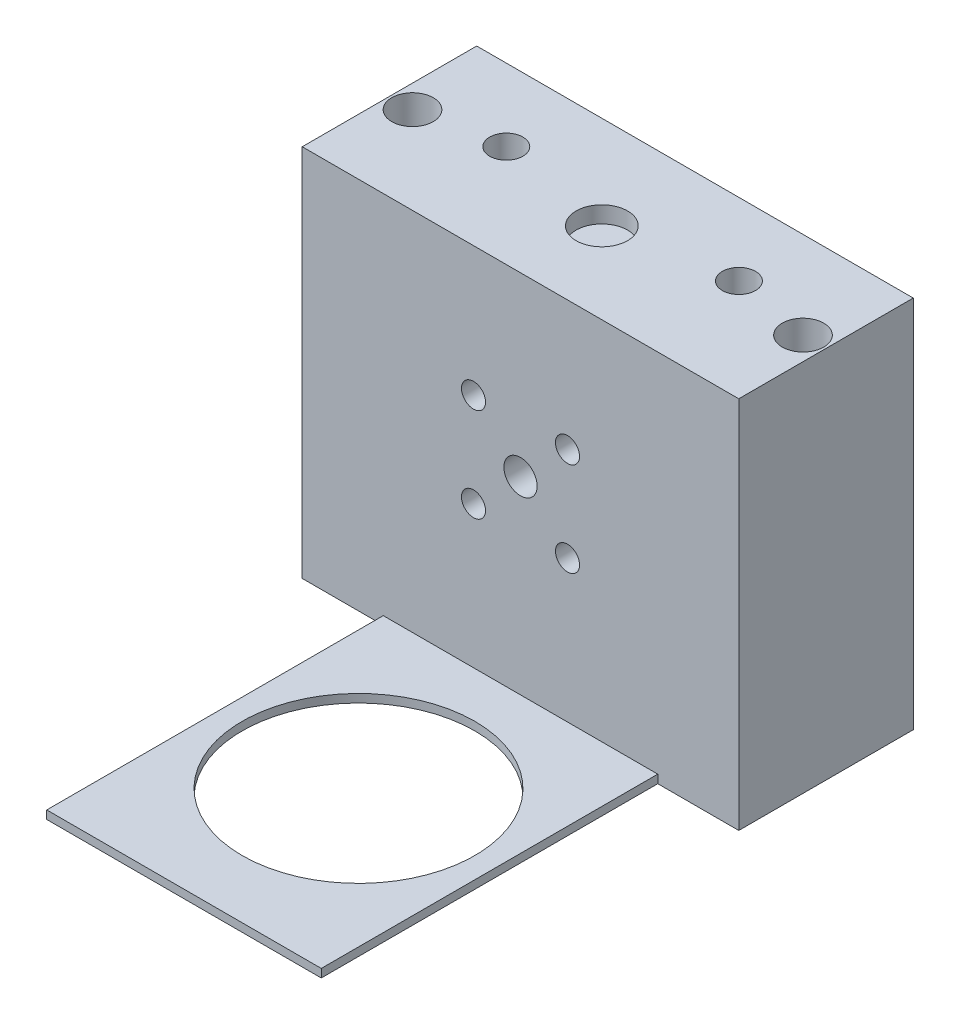
SolidWorks part; units mm, degrees
ref_plane "Front Plane" through (0, 0, 0) normal (0, 0, 1) x (1, 0, 0)
ref_plane "Top Plane" through (0, 0, 0) normal (0, 1, 0) x (1, 0, 0)
ref_plane "Right Plane" through (0, 0, 0) normal (1, 0, 0) x (0, 0, -1)
sketch "Sketch1" plane through (0, 0, 0) normal (0, 1, 0) x (1, 0, 0)
  line L0 (-23.5, 0) -> (23.5, 0) construction
  line L1 (-26.27, -10.5) -> (26.27, -10.5)
  line L2 (-26.27, -10.5) -> (-26.27, 10.5)
  line L3 (-26.27, 10.5) -> (26.27, 10.5)
  line L4 (26.27, -10.5) -> (26.27, 10.5)
  line L5 (-26.27, -10.5) -> (26.27, 10.5) construction
  line L6 (-26.27, 10.5) -> (26.27, -10.5) construction
  circle A0 centre (23.5, 0) radius 2.5
  circle A1 centre (-23.5, 0) radius 2.5
  point P0 (0, 0)
  dimension "D4" = 5
  dimension "D1" = 21
  dimension "D2" = 52.54
  dimension "D3" = 47
extrude "Boss-Extrude1" add sketch "Sketch1" along normal blind 45
sketch "Sketch2" plane through (0, 0, -10.5) normal (0, 0, -1) x (-1, 0, 0)
  line L0 (-26.27, 45) -> (26.27, 45) construction
  circle A0 centre (0, 23.75) radius 2
  point P2 (0, 0)
  dimension "D1" = 4
  dimension "D2" = 21.25
extrude "Cut-Extrude1" cut sketch "Sketch2" against normal through all
sketch "Sketch3" plane through (0, 45, 0) normal (0, 1, 0) x (1, 0, 0)
  line L0 (-14, 1.79) -> (14, 1.79) construction
  circle A0 centre (-14, 1.79) radius 2
  circle A1 centre (14, 1.79) radius 2
  point P4 (0, 1.79)
  point P5 (0, 0)
  point P11 (0, 0)
  dimension "D1" = 4
  dimension "D2" = 28
  dimension "D3" = 1.79
extrude "Cut-Extrude2" cut sketch "Sketch3" against normal blind 5
sketch "Sketch4" plane through (0, 0, -10.5) normal (0, 0, -1) x (-1, 0, 0)
  line L0 (-5.6569, 18.0931) -> (5.6569, 18.0931) construction
  line L1 (5.6569, 18.0931) -> (5.6569, 29.4069) construction
  line L2 (5.6569, 29.4069) -> (-5.6569, 29.4069) construction
  line L3 (-5.6569, 29.4069) -> (-5.6569, 18.0931) construction
  line L4 (-26.27, 45) -> (26.27, 45) construction
  circle A0 centre (0, 23.75) radius 8 construction
  point P3 (-5.6569, 18.0931)
  point P4 (-5.6569, 29.4069)
  point P5 (5.6569, 29.4069)
  point P6 (5.6569, 18.0931)
  point P11 (5.6569, 18.6569)
  point P12 (5.6569, 18.6569)
  point P13 (3.7347, 5.9252)
  dimension "D1" = 16
  dimension "D2" = 0
hole_wizard "CBORE for M2.5 Hex Socket Head Cap Screw1" positions "3DSketch1" profile "Sketch5" counterbore size "M2.5" standard "ISO" end condition through all
sketch3d "3DSketch1"
  point P0 (-5.6569, 18.0931, -10.5)
  point P3 (5.6569, 18.0931, -10.5)
  point P6 (5.6569, 29.4069, -10.5)
  point P9 (-5.6569, 29.4069, -10.5)
sketch "Sketch5" plane through (-5.6569, 18.0931, -10.5) normal (1, 0, 0) x (0, 1, 0)
  line L0 (0, 0) -> (0, 21)
  line L1 (0, 21) -> (1.45, 21)
  line L3 (1.45, 21) -> (1.45, 16)
  line L4 (1.45, 16) -> (2.75, 16)
  line L5 (2.75, 16) -> (2.75, 0)
  line L7 (2.75, 0) -> (0, 0)
  line L11 (0, -6.35) -> (0, 107.95) construction
  dimension "Thru Hole Dia." = 2.9
  dimension "Thru Hole Depth" = 21
  dimension "C'Bore Dia." = 5.5
  dimension "C'Bore Depth" = 16
sketch "Sketch6" plane through (0, 45, 0) normal (0, 1, 0) x (1, 0, 0)
  line L0 (-26.27, -10.5) -> (26.27, -10.5) construction
  circle A0 centre (0, -0.71) radius 3.1
  point P2 (0, 0)
  dimension "D1" = 6.2
  dimension "D2" = 9.79
extrude "Cut-Extrude3" cut sketch "Sketch6" against normal blind 2
sketch "Sketch7" plane through (0, 0, 0) normal (0, -1, 0) x (1, 0, 0)
  line L0 (-26.27, 10.5) -> (26.27, 10.5) construction
  line L1 (-16.52, 10.5) -> (16.52, 10.5)
  line L2 (-16.52, 10.5) -> (-16.52, 51)
  line L3 (-16.52, 51) -> (16.52, 51)
  line L4 (16.52, 10.5) -> (16.52, 51)
  circle A0 centre (0, 30) radius 14
  point P6 (0, 10.5)
  point P10 (0, 0)
  dimension "D1" = 28
  dimension "D2" = 19.5
  dimension "D3" = 21
  dimension "D4" = 16.52
extrude "Boss-Extrude2" add sketch "Sketch7" against normal blind 1
